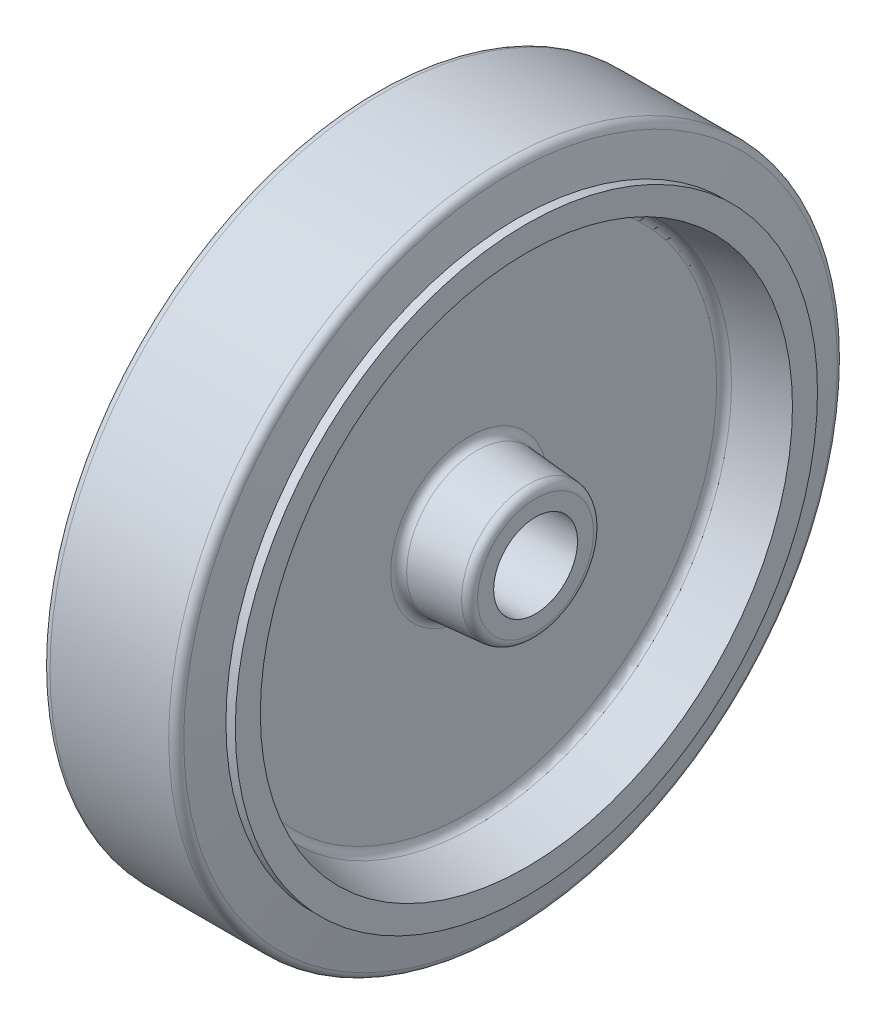
SolidWorks part; units mm, degrees
ref_plane "Front Plane" through (0, 0, 0) normal (0, 0, 1) x (1, 0, 0)
ref_plane "Top Plane" through (0, 0, 0) normal (0, 1, 0) x (1, 0, 0)
ref_plane "Right Plane" through (0, 0, 0) normal (1, 0, 0) x (0, 0, -1)
sketch "Sketch1" plane through (0, 0, 0) normal (0, 0, 1) x (1, 0, 0)
  line L0 (-15.9, -80) -> (15.9, -80)
  line L1 (-15.9, -80) -> (-17.75, -69.8)
  line L2 (20, -63.8) -> (6.3, -60.95)
  line L3 (6.3, -60.95) -> (6.3, -17)
  line L4 (6.3, -17) -> (22.2, -15.75)
  line L5 (22.2, -15.75) -> (22.2, -10.05)
  line L6 (0, -80) -> (0, 0) construction
  line L7 (0, 0) -> (22.2, 0) construction
  line L8 (22.2, -10.05) -> (-22.2, -10.05)
  line L9 (-22.2, -15.75) -> (-22.2, -10.05)
  line L10 (-6.3, -17) -> (-22.2, -15.75)
  line L11 (-6.3, -60.95) -> (-6.3, -17)
  line L12 (-20, -63.8) -> (-6.3, -60.95)
  line L13 (-17.75, -69.8) -> (-20, -69.8)
  line L14 (-20, -69.8) -> (-20, -63.8)
  line L15 (15.9, -80) -> (17.75, -69.8)
  line L16 (17.75, -69.8) -> (20, -69.8)
  line L17 (20, -69.8) -> (20, -63.8)
  point P12 (0, -10.05)
  dimension "D1" = 44.4
  dimension "D2" = 40
  dimension "D3" = 20.1
  dimension "D4" = 31.5
  dimension "D5" = 160
  dimension "D6" = 6
  dimension "D7" = 15.9
  dimension "D8" = 1.85
  dimension "D9" = 2.25
  dimension "D10" = 16.2
  dimension "D11" = 2.85
  dimension "D12" = 34
revolve "Revolve1" add sketch "Sketch1" angle 360 about L7
fillet "Fillet1" radius 2 8 edges at (6.3, 0, 60.95) (6.3, 0, 17) (-6.3, 0, 17) (-6.3, 0, 60.95) (22.2, 0, 15.75) (-22.2, 0, 15.75) (-15.9, 0, 80) (15.9, 0, 80)
move or copy body "Body-Move/Copy1" [suppressed] bodies to move or copy 101
